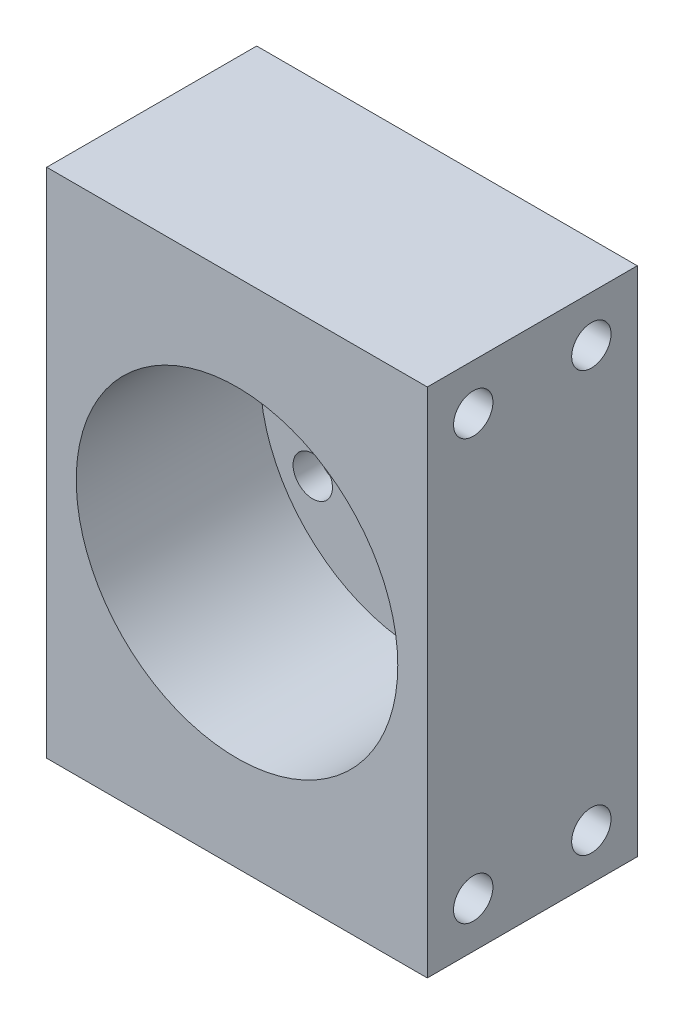
SolidWorks part; units mm, degrees
ref_plane "前视基准面" through (0, 0, 0) normal (0, 0, 1) x (1, 0, 0)
ref_plane "上视基准面" through (0, 0, 0) normal (0, 1, 0) x (1, 0, 0)
ref_plane "右视基准面" through (0, 0, 0) normal (1, 0, 0) x (0, 0, -1)
sketch "草图1" plane through (0, 0, 0) normal (0, 0, 1) x (1, 0, 0)
  line L1 (-1.138, -14.5) -> (27.862, -14.5)
  line L2 (-1.138, -14.5) -> (-1.138, 24.5)
  line L3 (-1.138, 24.5) -> (27.862, 24.5)
  line L4 (27.862, -14.5) -> (27.862, 24.5)
  point P0 (0, 0)
  dimension "D1" = 39
  dimension "D2" = 29
extrude "凸台-拉伸1" add sketch "草图1" along normal blind 16
sketch "草图2" plane through (0, 0, 16) normal (0, 0, 1) x (1, 0, 0)
  line L0 (13.362, 24.5) -> (13.362, -14.5) construction
  line L1 (27.862, 24.5) -> (-1.138, 24.5) construction
  line L2 (-1.138, 5) -> (27.862, 5) construction
  line L4 (-1.138, 24.5) -> (-1.138, -14.5) construction
  line L5 (27.862, -14.5) -> (27.862, 24.5) construction
  line L6 (-1.138, -14.5) -> (27.862, -14.5) construction
  circle A0 centre (13.362, 5) radius 12.25
  dimension "D1" = 24.5
extrude "切除-拉伸1" cut sketch "草图2" against normal blind 14
sketch "草图3" plane through (0, 0, 0) normal (0, 0, -1) x (-1, 0, 0)
  line L0 (-13.362, 24.5) -> (-13.362, -14.6917) construction
  line L1 (-27.862, 24.5) -> (1.138, 24.5) construction
  line L2 (1.138, 5) -> (-27.862, 5) construction
  line L4 (1.138, 24.5) -> (1.138, -14.5) construction
  line L5 (-27.862, -14.5) -> (-27.862, 24.5) construction
  line L6 (-13.362, -14.6917) -> (-13.362, -14.5) construction
  line L7 (1.138, -14.5) -> (-27.862, -14.5) construction
  circle A0 centre (-13.362, 5) radius 6.75
  dimension "D1" = 13.5
extrude "切除-拉伸2" cut sketch "草图3" against normal blind 14
sketch "草图4" plane through (0, 0, 0) normal (0, 0, -1) x (-1, 0, 0)
  circle A0 centre (-13.362, 5) radius 9.5 construction
  circle A1 centre (-13.362, 14.5) radius 1.5
  circle A2 centre (-5.1348, 9.75) radius 1.5
  circle A3 centre (-5.1348, 0.25) radius 1.5
  circle A4 centre (-13.362, -4.5) radius 1.5
  circle A5 centre (-21.5893, 0.25) radius 1.5
  circle A6 centre (-21.5893, 9.75) radius 1.5
  point P18 (-13.362, 5)
  dimension "D1" = 19
  dimension "D2" = 3
  dimension "D3" = 6
extrude "切除-拉伸3" cut sketch "草图4" against normal blind 14
sketch "草图5" plane through (-1.138, 0, 0) normal (-1, 0, 0) x (0, 0, 1)
  line L0 (8, 24.5) -> (8, -14.5) construction
  line L1 (16, 24.5) -> (0, 24.5) construction
  line L2 (16, -14.5) -> (0, -14.5) construction
  line L3 (0, 5) -> (16, 5) construction
  line L8 (0, 24.5) -> (0, -14.5) construction
  line L9 (16, 24.5) -> (16, -14.5) construction
  circle A0 centre (12.5, 21) radius 1.5
  circle A4 centre (3.5, 21) radius 1.5
  circle A5 centre (12.5, -11) radius 1.5
  circle A6 centre (3.5, -11) radius 1.5
  point P7 (8, 0)
  dimension "D3" = 3
  dimension "D2" = 3.5
  dimension "D1" = 3.5
extrude "切除-拉伸4" cut sketch "草图5" against normal blind 10
sketch "草图6" plane through (27.862, 0, 0) normal (1, 0, 0) x (0, 0, -1)
  line L0 (0, 5) -> (-16, 5) construction
  line L1 (0, -14.5) -> (0, 24.5) construction
  line L2 (-16, -14.5) -> (-16, 24.5) construction
  line L3 (-8, -14.5) -> (-8, 24.5) construction
  line L4 (-16, -14.5) -> (0, -14.5) construction
  line L5 (-16, 24.5) -> (0, 24.5) construction
  circle A10 centre (-12.5, -11) radius 1.5
  circle A11 centre (-3.5, -11) radius 1.5
  circle A12 centre (-3.5, -11) radius 1.5
  circle A13 centre (-3.5, 21) radius 1.5
  circle A14 centre (-12.5, 21) radius 1.5
  dimension "D1" = 0
extrude "切除-拉伸6" cut sketch "草图6" against normal blind 10
